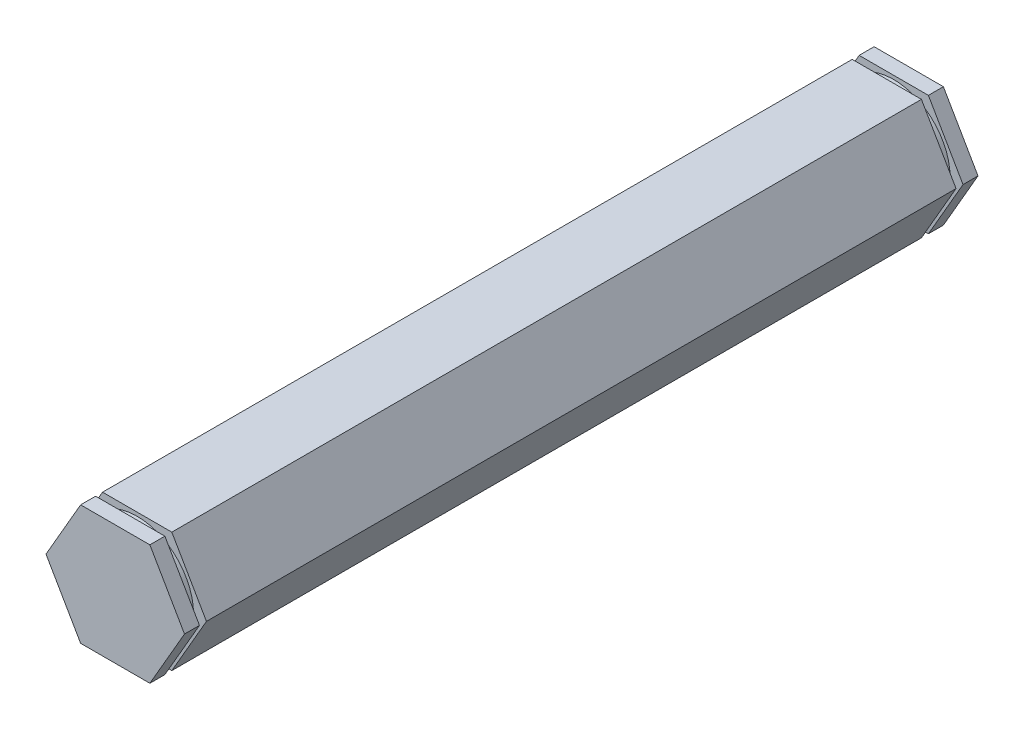
SolidWorks part; units mm, degrees
ref_plane "Front Plane" through (0, 0, 0) normal (0, 0, 1) x (1, 0, 0)
ref_plane "Top Plane" through (0, 0, 0) normal (0, 1, 0) x (1, 0, 0)
ref_plane "Right Plane" through (0, 0, 0) normal (1, 0, 0) x (0, 0, -1)
ref_plane "Plane1" through (0, 0, 31.75) normal (0, 0, 1) x (1, 0, 0)
sketch "Sketch1" plane through (0, 0, 31.75) normal (0, 0, 1) x (1, 0, 0)
  line L7 (7.3323, 0) -> (3.6662, 6.35)
  line L8 (3.6662, 6.35) -> (-3.6662, 6.35)
  line L9 (-3.6662, 6.35) -> (-7.3323, 0)
  line L10 (-7.3323, 0) -> (-3.6662, -6.35)
  line L11 (-3.6662, -6.35) -> (3.6662, -6.35)
  line L12 (3.6662, -6.35) -> (7.3323, 0)
  circle A0 centre (0, 0) radius 6.35 construction
  dimension "D1" = 12.7
extrude "Boss-Extrude1" add sketch "Sketch1" against normal blind 84.0232
ref_plane "Plane2" through (0, 0, 30.1625) normal (0, 0, 1) x (1, 0, 0)
sketch "Sketch2" plane through (0, 0, 30.1625) normal (0, 0, 1) x (1, 0, 0)
  line L1 (7.3323, 0) -> (3.6662, 6.35)
  line L2 (3.6662, 6.35) -> (-3.6662, 6.35)
  line L3 (-3.6662, 6.35) -> (-7.3323, 0)
  line L4 (-7.3323, 0) -> (-3.6662, -6.35)
  line L5 (-3.6662, -6.35) -> (3.6662, -6.35)
  line L6 (3.6662, -6.35) -> (7.3323, 0)
  circle A0 centre (0, 0) radius 5.969
  circle A1 centre (0, 0) radius 6.35 construction
  dimension "D1" = 12.7
  dimension "D2" = 11.938
extrude "Cut-Extrude1" cut sketch "Sketch2" against normal blind 0.7366 contours L5 L6 L1 L2 L3 L4 A0
pattern_linear "LPattern1" count 2 spacing 80.1116 along (0, 0, -1) of "Cut-Extrude1"
equation "\"0n\"=0.1"
